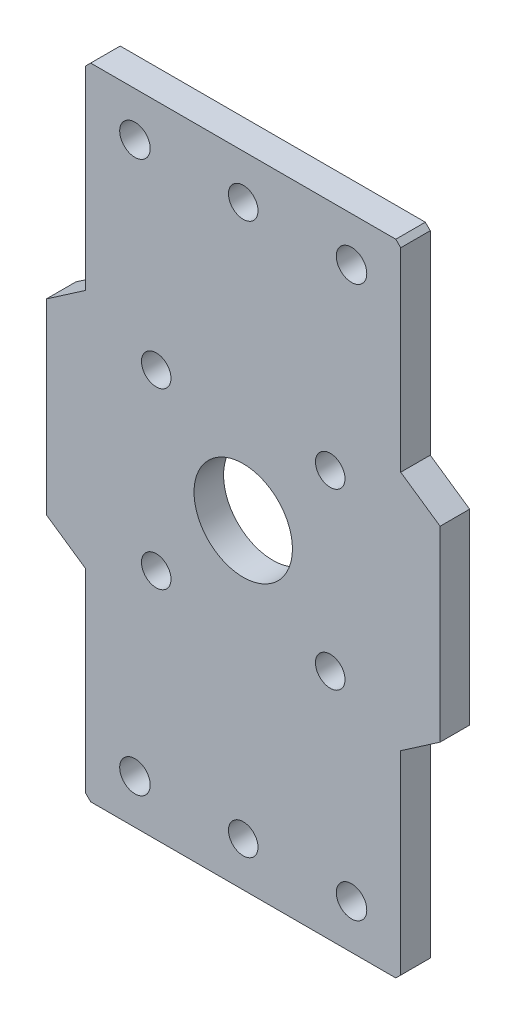
SolidWorks part; units mm, degrees
material "Thornel VCB-20 Karbon Kumaş"
ref_plane "Ön Düzlem" through (0, 0, 0) normal (0, 0, 1) x (1, 0, 0)
ref_plane "Üst Düzlem" through (0, 0, 0) normal (0, 1, 0) x (1, 0, 0)
ref_plane "Sağ Düzlem" through (0, 0, 0) normal (1, 0, 0) x (0, 0, -1)
sketch "Çizim1" plane through (0, 0, 0) normal (0, 0, 1) x (1, 0, 0)
  line L1 (-12, 51.5) -> (-9.5, 51.5)
  line L2 (-20, 33.5) -> (-20, 15.75)
  line L3 (-8.5, -51.5) -> (8.5, -51.5)
  line L5 (7.5, 49.5) -> (-7.5, 49.5)
  line L8 (7.5, 49.5) -> (-7.5, 49.5)
  line L11 (0, 55.8028) -> (0, -67.5402) construction
  line L12 (-9.5, 51.5) -> (-7.5, 49.5)
  line L17 (-16, 13) -> (-16, 0)
  line L20 (-16, 47.5) -> (-12, 51.5)
  line L21 (-16, 47.5) -> (-16, 37.5)
  line L22 (-20, 15.75) -> (-20, 34.75)
  line L23 (-12.5, -4) -> (-12.5, -12)
  line L24 (-16, 13) -> (-20, 15.75)
  line L25 (-20, 34.75) -> (-16, 37.5)
  line L26 (-12.5, -12) -> (-13.25, -12.75)
  line L27 (-16, 0) -> (-14, -2)
  line L28 (-14, -2) -> (-14, -2.5)
  line L29 (-14, -2.5) -> (-12.5, -4)
  line L30 (-13.25, -12.75) -> (-13.25, -18.75)
  line L31 (-13.25, -18.75) -> (-12.5, -19.5)
  line L32 (-12.5, -27.5) -> (-13.25, -28.25)
  line L33 (-13.25, -34.25) -> (-12.5, -35)
  line L34 (-13.25, -28.25) -> (-13.25, -34.25)
  line L35 (-12.5, -19.5) -> (-12.5, -27.5)
  line L36 (-12.5, -43) -> (-13.25, -43.75)
  line L37 (-12.5, -35) -> (-12.5, -43)
  line L38 (-13.25, -43.75) -> (-13.25, -48.2026)
  line L39 (-2.6244, -19.3001) -> (-2.6244, -21.3001)
  line L40 (8.5, -51.5) -> (-8.5, -51.5)
  line L41 (-8.5, -51.5) -> (-13.25, -48.2026)
  line L45 (3, 40.2449) -> (3.495, 39.7499)
  line L46 (3.495, 39.7499) -> (5.495, 39.7499)
  line L55 (-8.5, 41.7499) -> (-5.495, 39.7499)
  line L56 (-3.495, 46.7499) -> (-5.495, 46.7499)
  line L57 (-3, 46.255) -> (-3.495, 46.7499)
  line L58 (3, 46.255) -> (-3, 46.255)
  line L59 (-8.5, 44.7499) -> (-5.495, 46.7499)
  line L60 (-8.5, 41.7499) -> (-8.5, 44.7499)
  line L61 (-8.5, 41.7499) -> (-5.495, 39.7499)
  line L62 (-8.5, 43.2499) -> (-8.5, 41.7499)
  line L63 (-3.495, 39.7499) -> (-5.495, 39.7499)
  line L64 (-3, 40.2449) -> (-3.495, 39.7499)
  line L65 (3, 40.2449) -> (-3, 40.2449)
  line L66 (8.5, 43.2499) -> (8.5, 41.7499)
  line L67 (8.5, 41.7499) -> (5.495, 39.7499)
  line L68 (8.5, 41.7499) -> (8.5, 44.7499)
  line L69 (8.5, 44.7499) -> (5.495, 46.7499)
  line L70 (3, 46.255) -> (3.495, 46.7499)
  line L71 (3.495, 46.7499) -> (5.495, 46.7499)
  line L72 (8.5, 41.7499) -> (5.495, 39.7499)
  line L82 (8.5, -51.5) -> (13.25, -48.2026)
  line L83 (13.25, -43.75) -> (13.25, -48.2026)
  line L84 (12.5, -35) -> (12.5, -43)
  line L85 (12.5, -43) -> (13.25, -43.75)
  line L86 (12.5, -19.5) -> (12.5, -27.5)
  line L87 (13.25, -28.25) -> (13.25, -34.25)
  line L88 (13.25, -34.25) -> (12.5, -35)
  line L89 (12.5, -27.5) -> (13.25, -28.25)
  line L90 (13.25, -18.75) -> (12.5, -19.5)
  line L91 (13.25, -12.75) -> (13.25, -18.75)
  line L92 (14, -2.5) -> (12.5, -4)
  line L93 (14, -2) -> (14, -2.5)
  line L94 (16, 0) -> (14, -2)
  line L95 (12.5, -12) -> (13.25, -12.75)
  line L96 (20, 34.75) -> (16, 37.5)
  line L97 (16, 13) -> (20, 15.75)
  line L98 (12.5, -4) -> (12.5, -12)
  line L99 (20, 15.75) -> (20, 34.75)
  line L100 (16, 47.5) -> (16, 37.5)
  line L101 (16, 47.5) -> (12, 51.5)
  line L102 (16, 13) -> (16, 0)
  line L103 (9.5, 51.5) -> (7.5, 49.5)
  line L104 (20, 33.5) -> (20, 15.75)
  line L105 (12, 51.5) -> (9.5, 51.5)
  line L106 (-9.1295, -18.8051) -> (-9.6244, -19.3001)
  line L107 (-4.6244, -7.3051) -> (-2.6244, -10.3101)
  line L108 (-7.6244, -7.3051) -> (-9.6244, -10.3101)
  line L109 (-9.6244, -12.3101) -> (-9.6244, -10.3101)
  line L110 (-7.6244, -24.3051) -> (-9.6244, -21.3001)
  line L111 (-6.1244, -24.3051) -> (-7.6244, -24.3051)
  line L112 (-7.6244, -7.3051) -> (-4.6244, -7.3051)
  line L113 (-9.1295, -12.8051) -> (-9.6244, -12.3101)
  line L114 (-7.6244, -24.3051) -> (-4.6244, -24.3051)
  line L115 (-9.1295, -12.8051) -> (-9.1295, -18.8051)
  line L116 (-3.1194, -12.8051) -> (-3.1194, -18.8051)
  line L117 (-2.6244, -12.3101) -> (-2.6244, -10.3101)
  line L118 (-9.6244, -19.3001) -> (-9.6244, -21.3001)
  line L119 (-7.6244, -24.3051) -> (-9.6244, -21.3001)
  line L120 (-7.6244, -7.3051) -> (-9.6244, -10.3101)
  line L121 (-3.1194, -18.8051) -> (-2.6244, -19.3001)
  line L122 (-3.1194, -12.8051) -> (-2.6244, -12.3101)
  line L123 (-4.6244, -24.3051) -> (-2.6244, -21.3001)
  line L124 (-6.1244, -7.3051) -> (-7.6244, -7.3051)
  line L125 (6.1244, -7.3051) -> (7.6244, -7.3051)
  line L126 (4.6244, -24.3051) -> (2.6244, -21.3001)
  line L127 (3.1194, -12.8051) -> (2.6244, -12.3101)
  line L128 (3.1194, -18.8051) -> (2.6244, -19.3001)
  line L129 (7.6244, -7.3051) -> (9.6244, -10.3101)
  line L130 (7.6244, -24.3051) -> (9.6244, -21.3001)
  line L131 (9.6244, -19.3001) -> (9.6244, -21.3001)
  line L132 (2.6244, -12.3101) -> (2.6244, -10.3101)
  line L133 (3.1194, -12.8051) -> (3.1194, -18.8051)
  line L134 (9.1295, -12.8051) -> (9.1295, -18.8051)
  line L135 (7.6244, -24.3051) -> (4.6244, -24.3051)
  line L136 (9.1295, -12.8051) -> (9.6244, -12.3101)
  line L137 (7.6244, -7.3051) -> (4.6244, -7.3051)
  line L138 (6.1244, -24.3051) -> (7.6244, -24.3051)
  line L139 (7.6244, -24.3051) -> (9.6244, -21.3001)
  line L140 (9.6244, -12.3101) -> (9.6244, -10.3101)
  line L141 (7.6244, -7.3051) -> (9.6244, -10.3101)
  line L142 (4.6244, -7.3051) -> (2.6244, -10.3101)
  line L143 (9.1295, -18.8051) -> (9.6244, -19.3001)
  line L144 (2.6244, -19.3001) -> (2.6244, -21.3001)
  line L145 (3.1194, -42.1051) -> (2.6244, -42.6001)
  line L146 (7.6244, -30.6051) -> (9.6244, -33.6101)
  line L147 (-3.1194, -36.1051) -> (-3.1194, -42.1051)
  line L148 (-4.6244, -47.6051) -> (-2.6244, -44.6001)
  line L149 (9.6244, -35.6101) -> (9.6244, -33.6101)
  line L150 (3.1194, -36.1051) -> (2.6244, -35.6101)
  line L151 (7.6244, -30.6051) -> (9.6244, -33.6101)
  line L152 (9.1295, -36.1051) -> (9.1295, -42.1051)
  line L153 (7.6244, -30.6051) -> (4.6244, -30.6051)
  line L154 (-6.1244, -47.6051) -> (-7.6244, -47.6051)
  line L155 (7.6244, -47.6051) -> (4.6244, -47.6051)
  line L156 (9.1295, -42.1051) -> (9.6244, -42.6001)
  line L157 (-2.6244, -42.6001) -> (-2.6244, -44.6001)
  line L158 (-7.6244, -30.6051) -> (-9.6244, -33.6101)
  line L159 (4.6244, -47.6051) -> (2.6244, -44.6001)
  line L160 (-7.6244, -47.6051) -> (-9.6244, -44.6001)
  line L161 (-7.6244, -30.6051) -> (-9.6244, -33.6101)
  line L162 (4.6244, -30.6051) -> (2.6244, -33.6101)
  line L163 (-7.6244, -30.6051) -> (-4.6244, -30.6051)
  line L164 (-7.6244, -47.6051) -> (-4.6244, -47.6051)
  line L165 (-7.6244, -47.6051) -> (-9.6244, -44.6001)
  line L166 (6.1244, -47.6051) -> (7.6244, -47.6051)
  line L167 (-9.6244, -42.6001) -> (-9.6244, -44.6001)
  line L168 (3.1194, -36.1051) -> (3.1194, -42.1051)
  line L169 (-2.6244, -35.6101) -> (-2.6244, -33.6101)
  line L170 (7.6244, -47.6051) -> (9.6244, -44.6001)
  line L171 (-9.1295, -36.1051) -> (-9.6244, -35.6101)
  line L172 (-3.1194, -42.1051) -> (-2.6244, -42.6001)
  line L173 (2.6244, -42.6001) -> (2.6244, -44.6001)
  line L174 (-9.6244, -35.6101) -> (-9.6244, -33.6101)
  line L175 (-3.1194, -36.1051) -> (-2.6244, -35.6101)
  line L176 (-4.6244, -30.6051) -> (-2.6244, -33.6101)
  line L177 (-9.1295, -36.1051) -> (-9.1295, -42.1051)
  line L178 (7.6244, -47.6051) -> (9.6244, -44.6001)
  line L179 (-9.1295, -42.1051) -> (-9.6244, -42.6001)
  line L180 (6.1244, -30.6051) -> (7.6244, -30.6051)
  line L181 (9.6244, -42.6001) -> (9.6244, -44.6001)
  line L182 (2.6244, -35.6101) -> (2.6244, -33.6101)
  line L183 (-6.1244, -30.6051) -> (-7.6244, -30.6051)
  line L184 (9.1295, -36.1051) -> (9.6244, -35.6101)
  circle A2 centre (-11, 48.25) radius 1
  circle A3 centre (-11, -0.75) radius 1
  circle A10 centre (11, -0.75) radius 1
  circle A11 centre (11, 48.25) radius 1
  point P0 (0, 0)
  point P1 (0, -51.5)
  point P18 (0, 15.75)
  point P21 (0, 15.75)
  point P43 (0, -51.5)
  point P45 (0, 24.755)
  point P54 (0, 24.755)
  point P80 (0, 47.4999)
  point P87 (0, 40.2449)
  point P94 (0, 46.255)
  point P100 (0, 1.2449)
  point P128 (0, 49.5)
  point P143 (-3.1194, -15.8051)
  point P165 (3.1194, -15.8051)
  point P181 (-3.1194, -39.1051)
  point P203 (3.1194, -39.1051)
  dimension "D1" = 13
extrude "Yükseklik-Ekstrüzyon1" add sketch "Çizim1" along normal blind 3
sketch "Çizim2" plane through (0, 0, 3) normal (0, 0, 1) x (1, 0, 0)
  line L0 (-12.5, -4) -> (12.5, -4)
  line L1 (-12.5, -4) -> (-44.1479, -53.0588)
  line L2 (-44.1479, -53.0588) -> (17.3593, -71.305)
  line L3 (17.3593, -71.305) -> (38.5484, -28.5294)
  line L4 (38.5484, -28.5294) -> (12.5, -4)
extrude "Kes-Ekstrüzyon1" cut sketch "Çizim2" against normal blind 10
sketch "Çizim3" plane through (0, 0, 3) normal (0, 0, 1) x (1, 0, 0)
  line L0 (9.5, 51.5) -> (-9.5, 51.5)
  line L1 (-9.5, 51.5) -> (-7.5, 49.5)
  line L2 (-7.5, 49.5) -> (7.5, 49.5)
  line L3 (7.5, 49.5) -> (9.5, 51.5)
extrude "Yükseklik-Ekstrüzyon2" add sketch "Çizim3" against normal up to surface (3 mm away) up to face at (0, 43.2499, 0)
sketch "Çizim4" plane through (0, 0, 3) normal (0, 0, 1) x (1, 0, 0)
  line L0 (0, 32.255) -> (0, 17.255) construction
  circle A0 centre (0, 24.755) radius 23.75
  dimension "D1" = 47.5
sketch "Çizim6" plane through (0, 0, 3) normal (0, 0, 1) x (1, 0, 0)
  line L0 (-16, 47.5) -> (-16, 54.5)
  line L1 (16, 47.5) -> (16, 54.5)
  line L6 (-16, 54.5) -> (-12, 58.5)
  line L7 (-12, 58.5) -> (12, 58.5)
  line L8 (12, 58.5) -> (16, 54.5)
  line L9 (-16, 47.5) -> (-9.9442, 45.3975)
  line L10 (-9.9442, 45.3975) -> (-4.1363, 49.0781)
  line L11 (-4.1363, 49.0781) -> (6.2301, 48.369)
  line L12 (6.2301, 48.369) -> (12.5108, 45.9378)
  line L13 (12.5108, 45.9378) -> (16, 47.5)
  line L14 (-12, 51.5) -> (12, 51.5) construction
  line L15 (0, 51.5) -> (0, 58.5) construction
  circle A2 centre (11, 53.25) radius 1.55
  circle A3 centre (-11, 53.25) radius 1.55
  dimension "D2" = 3.1
  dimension "D3" = 3.1
  dimension "D4" = 135
  dimension "D5" = 7
  dimension "D1" = 24
  dimension "D6" = 1.75
  dimension "D7" = 1.75
  dimension "D8" = 7
extrude "Yükseklik-Ekstrüzyon4" add sketch "Çizim6" against normal up to surface (3 mm away) up to face at (0, 43.2499, 0)
sketch "Çizim8" plane through (0, 0, 3) normal (0, 0, 1) x (1, 0, 0)
  line L0 (-16, 0) -> (-16, -2)
  line L1 (16, 0) -> (16, -2)
  line L2 (-12.5, -6) -> (12.5, -6)
  line L3 (12.5, -4) -> (-12.5, -4) construction
  line L4 (-12.5, -6) -> (-16, -2)
  line L5 (16, -2) -> (12.5, -6)
  line L6 (-12.5, -4) -> (-12.5, -6) construction
  line L7 (12.5, -4) -> (12.5, -6) construction
  line L8 (-11, -0.75) -> (-11, -2.75) construction
  line L9 (11, -0.75) -> (11, -2.75) construction
  line L10 (-16, 0) -> (-11.4599, 2.5304)
  line L11 (-11.4599, 2.5304) -> (-3.5894, -1.1635)
  line L12 (-3.5894, -1.1635) -> (6.8531, -1.1635)
  line L13 (6.8531, -1.1635) -> (12.0011, 1.7057)
  line L14 (12.0011, 1.7057) -> (16, 0)
  circle A4 centre (-11, -2.75) radius 1.55
  circle A5 centre (11, -2.75) radius 1.55
  dimension "D4" = 3.1
  dimension "D1" = 2
  dimension "D2" = 2
  dimension "D3" = 2
sketch "Çizim9" plane through (0, 0, 3) normal (0, 0, 1) x (1, 0, 0)
  line L1 (-12.2111, 1.1499) -> (-9.4463, 1.1499)
  line L2 (-12.2111, 1.1499) -> (-12.2111, -1.7499)
  line L3 (-12.2111, -1.7499) -> (-9.4463, -1.7499)
  line L4 (-9.4463, 1.1499) -> (-9.4463, -1.7499)
  line L5 (9.7728, 0.7115) -> (12.3084, 0.7115)
  line L6 (9.7728, 0.7115) -> (9.7728, -1.919)
  line L7 (9.7728, -1.919) -> (12.3084, -1.919)
  line L8 (12.3084, 0.7115) -> (12.3084, -1.919)
  circle A0 centre (11, -2.75) radius 1.55 construction
extrude "Yükseklik-Ekstrüzyon5" add sketch "Çizim9" against normal up to surface (3 mm away) up to face at (0, 20.55, 0)
extrude "Yükseklik-Ekstrüzyon6" add sketch "Çizim8" against normal up to surface (3 mm away) contours A4 | A5 | L14 L1 L5 L2 L4 L0 L10 L11 L12 L13 up to face at (-11, -1.7499, 0)
sketch "Çizim10" plane through (0, 0, 3) normal (0, 0, 1) x (1, 0, 0)
  circle A0 centre (-11, -2.75) radius 1.55
  circle A1 centre (11, -2.75) radius 1.55
  dimension "D1" = 3.1
  dimension "D2" = 3.1
extrude "Kes-Ekstrüzyon2" cut sketch "Çizim10" against normal blind 10
sketch "Çizim14" plane through (0, 0, 3) normal (0, 0, 1) x (1, 0, 0)
  line L0 (-20, 25.25) -> (20, 25.25) construction
  line L1 (-20, 15.75) -> (-20, 34.75) construction
  line L2 (20, 15.75) -> (20, 34.75) construction
  line L3 (0, 25.25) -> (8.8388, 34.0888) construction
  line L4 (0, 25.25) -> (-8.8388, 34.0888) construction
  line L5 (0, 25.25) -> (8.8388, 16.4112) construction
  line L6 (0, 25.25) -> (-8.8388, 16.4112) construction
  circle A0 centre (0, 25.25) radius 12.5 construction
  circle A3 centre (8.8388, 34.0888) radius 1.5
  circle A4 centre (-8.8388, 16.4112) radius 1.5
  circle A5 centre (8.8388, 16.4112) radius 1.5
  circle A6 centre (-8.8388, 34.0888) radius 1.5
  dimension "D1" = 25
  dimension "D2" = 3
  dimension "D3" = 45
  dimension "D4" = 45
  dimension "D5" = 90
  dimension "D6" = 90
extrude "Kes-Ekstrüzyon3" cut sketch "Çizim14" against normal blind 10
sketch "Çizim15" plane through (0, 0, 3) normal (0, 0, 1) x (1, 0, 0)
  circle A0 centre (0, 25.25) radius 5
  dimension "D1" = 10
extrude "Kes-Ekstrüzyon4" cut sketch "Çizim15" against normal blind 10
sketch "Çizim17" plane through (0, 0, 3) normal (0, 0, 1) x (1, 0, 0)
  circle A0 centre (0, 25.25) radius 23.75
  dimension "D1" = 47.5
sketch "Çizim19" plane through (0, 0, 3) normal (0, 0, 1) x (1, 0, 0)
  line L0 (-16, -13) -> (-12, -17)
  line L1 (-16, -2) -> (16, -2)
  line L2 (-16, -2) -> (-16, -13)
  line L3 (-12, -17) -> (12, -17)
  line L4 (16, -2) -> (16, -13)
  line L5 (12, -17) -> (16, -13)
  point P1 (16, -17)
  point P2 (-16, -17)
  dimension "D1" = 15
  dimension "D2" = 32
extrude "Yükseklik-Ekstrüzyon7" add sketch "Çizim19" against normal blind 3
sketch "Çizim21" plane through (0, 0, 3) normal (0, 0, 1) x (1, 0, 0)
  line L0 (-20, 25.25) -> (20, 25.25) construction
  line L1 (-20, 15.75) -> (-20, 34.75) construction
  line L2 (20, 15.75) -> (20, 34.75) construction
sketch "Çizim22" plane through (0, 0, 3) normal (0, 0, 1) x (1, 0, 0)
  line L1 (-8.5, -12.1157) -> (-5.495, -14.1157)
  line L2 (-3.495, -14.1157) -> (-5.495, -14.1157)
  line L3 (-8.5, -9.1157) -> (-8.5, -12.1157)
  line L4 (-8.5, -9.1157) -> (-5.495, -7.1157)
  line L5 (-3.495, -7.1157) -> (-5.495, -7.1157)
  line L6 (3, -13.6207) -> (-3, -13.6207)
  line L7 (-3, -13.6207) -> (-3.495, -14.1157)
  line L8 (3, -13.6207) -> (3.495, -14.1157)
  line L9 (3.495, -14.1157) -> (5.495, -14.1157)
  line L10 (8.5, -12.1157) -> (5.495, -14.1157)
  line L11 (8.5, -9.1157) -> (8.5, -12.1157)
  line L12 (8.5, -9.1157) -> (5.495, -7.1157)
  line L13 (3.495, -7.1157) -> (5.495, -7.1157)
  line L19 (8.5, 41.7499) -> (8.5, 44.7499) construction
  line L27 (-8.5, 41.7499) -> (-8.5, 44.7499) construction
  line L30 (12, -17) -> (16, -13)
  line L31 (16, -13) -> (16, 13)
  line L32 (16, 13) -> (20, 15.75)
  line L33 (20, 15.75) -> (20, 34.75)
  line L34 (20, 34.75) -> (16, 37.5)
  line L35 (16, 37.5) -> (16, 54.5)
  line L36 (16, 54.5) -> (12, 58.5)
  line L37 (12, 58.5) -> (-12, 58.5)
  line L38 (-12, 58.5) -> (-16, 54.5)
  line L39 (-16, 54.5) -> (-16, 37.5)
  line L40 (-16, 37.5) -> (-20, 34.75)
  line L41 (-20, 34.75) -> (-20, 15.75)
  line L42 (-20, 15.75) -> (-16, 13)
  line L43 (-16, 13) -> (-16, -13)
  line L44 (-16, -13) -> (-12, -17)
  line L45 (-12, -17) -> (12, -17)
  line L46 (12, -17) -> (16, -13)
  line L47 (16, -13) -> (16, 13)
  line L48 (16, 13) -> (20, 15.75)
  line L49 (20, 15.75) -> (20, 34.75)
  line L50 (20, 34.75) -> (16, 37.5)
  line L51 (16, 37.5) -> (16, 54.5)
  line L52 (16, 54.5) -> (12, 58.5)
  line L53 (12, 58.5) -> (-12, 58.5)
  line L54 (-12, 58.5) -> (-16, 54.5)
  line L55 (-16, 54.5) -> (-16, 37.5)
  line L56 (-16, 37.5) -> (-20, 34.75)
  line L57 (-20, 34.75) -> (-20, 15.75)
  line L58 (-20, 15.75) -> (-16, 13)
  line L59 (-16, 13) -> (-16, -13)
  line L60 (-16, -13) -> (-12, -17)
  line L61 (-12, -17) -> (12, -17)
  line L67 (8.5, 41.7499) -> (8.5, 44.7499)
  line L75 (-8.5, 41.7499) -> (-8.5, 44.7499)
  line L79 (3, -7.6107) -> (-3, -7.6107)
  line L80 (-3, -7.6107) -> (-3.495, -7.1157)
  line L81 (3, -7.6107) -> (3.495, -7.1157)
  dimension "D1" = 0
extrude "Kes-Ekstrüzyon5" cut sketch "Çizim22" against normal blind 3 contours L81 L79 L80 L5 L4 L3 L1 L2 L7 L6 L8 L9 L10 L11 L12 L13
sketch "Çizim23" plane through (0, 0, 3) normal (0, 0, 1) x (1, 0, 0)
  circle A0 centre (-11, -2.75) radius 1.55
  circle A1 centre (11, -2.75) radius 1.55
extrude "Kes-Ekstrüzyon6" cut sketch "Çizim23" against normal blind 3
sketch "Çizim25" plane through (0, 0, 3) normal (0, 0, 1) x (1, 0, 0)
  line L1 (11, 53.25) -> (-11, 53.25) construction
  circle A0 centre (0, -2.75) radius 1.5
  circle A2 centre (0, 53.25) radius 1.5
  dimension "D1" = 3
  dimension "D2" = 3
extrude "Kes-Ekstrüzyon7" cut sketch "Çizim25" against normal blind 3
sketch "Çizim26" plane through (0, 0, 3) normal (0, 0, 1) x (1, 0, 0)
  line L0 (-16, 54.5) -> (-12, 58.5)
  line L1 (-12, 58.5) -> (-16, 58.5)
  line L2 (-16, 58.5) -> (-16, 54.5)
  line L3 (12, 58.5) -> (16, 54.5)
  line L4 (16, 54.5) -> (16, 58.5)
  line L5 (16, 58.5) -> (12, 58.5)
extrude "Yükseklik-Ekstrüzyon8" add sketch "Çizim26" against normal up to surface (3 mm away) up to face at (1.5, -2.75, 0)
sketch "Çizim27" plane through (0, 0, 3) normal (0, 0, 1) x (1, 0, 0)
  line L1 (-14, -7) -> (12, -7)
  line L2 (-14, -7) -> (-14, -17)
  line L3 (-14, -17) -> (12, -17)
  line L4 (12, -7) -> (12, -17)
extrude "Yükseklik-Ekstrüzyon9" add sketch "Çizim27" against normal up to surface (3 mm away) up to face at (1.5, -2.75, 0)
sketch "Çizim28" plane through (0, 0, 3) normal (0, 0, 1) x (1, 0, 0)
  line L0 (-16, 13) -> (-16, -13) construction
  line L1 (-16, -7.75) -> (16, -7.75)
  line L2 (-16, -7.75) -> (-16, -17.9335)
  line L3 (-16, -17.9335) -> (16, -17.9335)
  line L4 (16, -7.75) -> (16, -17.9335)
  line L5 (-14, -7) -> (-7.95, -7) construction
  dimension "D1" = 0.75
extrude "Kes-Ekstrüzyon8" cut sketch "Çizim28" against normal blind 10
sketch "Çizim29" plane through (0, 0, 3) normal (0, 0, 1) x (1, 0, 0)
  line L1 (-10.1116, 38.3798) -> (11.4863, 38.3798)
  line L2 (-10.1116, 38.3798) -> (-10.1116, 47.99)
  line L3 (-10.1116, 47.99) -> (11.4863, 47.99)
  line L4 (11.4863, 38.3798) -> (11.4863, 47.99)
extrude "Yükseklik-Ekstrüzyon11" add sketch "Çizim29" against normal up to surface (3 mm away) up to face at (0, 25.2917, 0)
sketch "Çizim30" plane through (0, 0, 3) normal (0, 0, 1) x (1, 0, 0)
  line L0 (-16, 58.5) -> (-16, 37.5) construction
  line L1 (-16, 57.75) -> (16, 57.75)
  line L2 (-16, 57.75) -> (-16, 58.5)
  line L3 (-16, 58.5) -> (16, 58.5)
  line L4 (16, 57.75) -> (16, 58.5)
  line L5 (-16, 13) -> (-16, -7.75) construction
  line L6 (16, -7.75) -> (-16, -7.75)
  line L7 (16, -7.75) -> (16, -7.25)
  line L8 (16, -7.25) -> (-16, -7.25)
  line L9 (-16, -7.75) -> (-16, -7.25)
  dimension "D1" = 0.75
  dimension "D2" = 0.5
extrude "Kes-Ekstrüzyon9" cut sketch "Çizim30" against normal blind 10
sketch "Çizim31" plane through (0, 0, 0) normal (0, 0, -1) x (-1, 0, 0)
  circle A0 centre (0, 25.25) radius 23.75
  dimension "D1" = 47.5
extrude "motor" [suppressed] add sketch "Çizim31" along normal blind 40
chamfer "Pah1" distance 0.5 4 edges at (16, 57.75, 1.5) (-16, 57.75, 1.5) (16, -7.25, 1.5) (-16, -7.25, 1.5)
